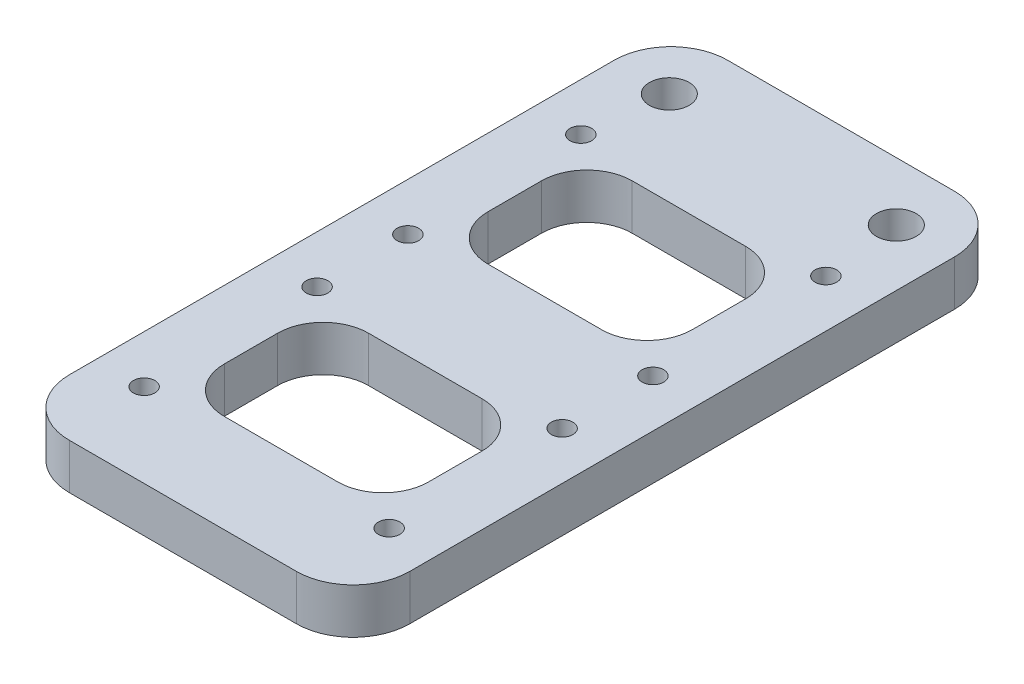
SolidWorks part; units mm, degrees
ref_plane "Front Plane" through (0, 0, 0) normal (0, 0, 1) x (1, 0, 0)
ref_plane "Top Plane" through (0, 0, 0) normal (0, 1, 0) x (1, 0, 0)
ref_plane "Right Plane" through (0, 0, 0) normal (1, 0, 0) x (0, 0, -1)
sketch "Sketch1" plane through (0, 0, 0) normal (0, 1, 0) x (1, 0, 0)
  line L1 (-15, -15) -> (15, -15)
  line L2 (-15, -15) -> (-15, 15)
  line L3 (-15, 15) -> (15, 15)
  line L4 (15, -15) -> (15, 15)
  line L5 (-15, -15) -> (15, 15) construction
  line L6 (-15, 15) -> (15, -15) construction
  point P0 (0, 0)
  dimension "D1" = 30
extrude "Boss-Extrude1" add sketch "Sketch1" along normal blind 4
sketch "Sketch3" plane through (0, 4, 0) normal (0, 1, 0) x (1, 0, 0)
  line L0 (15, -15) -> (15, 15) construction
  line L1 (-15, 15) -> (15, 15)
  line L2 (-15, 15) -> (-15, 43)
  line L3 (-15, 43) -> (15, 43)
  line L4 (15, 15) -> (15, 43)
  dimension "D1" = 28
extrude "Boss-Extrude2" add sketch "Sketch3" against normal up to surface (4 mm away) up to face at (0, 0, 0)
sketch "Sketch2" plane through (0, 4, 0) normal (0, 1, 0) x (1, 0, 0)
  line L0 (0, 0) -> (0, 50000) construction
  line L1 (-10.795, -7.62) -> (10.795, -7.62) construction
  line L2 (-10.795, -7.62) -> (-10.795, 7.62) construction
  line L3 (-10.795, 7.62) -> (10.795, 7.62) construction
  line L4 (10.795, -7.62) -> (10.795, 7.62) construction
  line L5 (-10.795, -7.62) -> (10.795, 7.62) construction
  line L6 (-10.795, 7.62) -> (10.795, -7.62) construction
  line L7 (-5, -6.3529) -> (5, -6.3529)
  line L8 (-9, -2.3529) -> (-9, 2.3529)
  line L9 (-5, 6.3529) -> (5, 6.3529)
  line L10 (9, -2.3529) -> (9, 2.3529)
  line L11 (-9, -6.3529) -> (10.795, 7.62) construction
  line L12 (-9, 6.3529) -> (9, -6.3529) construction
  line L13 (0, 23.24) -> (50000, 23.24) construction
  line L15 (-10.795, 15.62) -> (10.795, 15.62) construction
  line L16 (-10.795, 15.62) -> (-10.795, 30.86) construction
  line L17 (-10.795, 30.86) -> (10.795, 30.86) construction
  line L18 (10.795, 15.62) -> (10.795, 30.86) construction
  line L19 (-10.795, 15.62) -> (10.795, 30.86) construction
  line L20 (-10.795, 30.86) -> (10.795, 15.62) construction
  line L21 (-10, 37.86) -> (10, 37.86) construction
  line L23 (-10.795, 30.86) -> (10.795, 30.86) construction
  line L28 (-5, 16.8871) -> (5, 16.8871)
  line L29 (-9, 20.8871) -> (-9, 25.5929)
  line L30 (-5, 29.5929) -> (5, 29.5929)
  line L31 (9, 20.8871) -> (9, 25.5929)
  line L32 (-9, 16.8871) -> (9, 29.5929) construction
  line L33 (-9, 29.5929) -> (9, 16.8871) construction
  circle A0 centre (-10.795, -7.62) radius 0.95
  circle A1 centre (10.795, -7.62) radius 0.95
  circle A2 centre (10.795, 7.62) radius 0.95
  circle A3 centre (-10.795, 7.62) radius 0.95
  arc A4 (-5, -6.3529) -> (-9, -2.3529) centre (-5, -2.3529) cw
  arc A5 (5, -6.3529) -> (9, -2.3529) centre (5, -2.3529) ccw
  arc A6 (5, 6.3529) -> (9, 2.3529) centre (5, 2.3529) cw
  arc A7 (-9, 2.3529) -> (-5, 6.3529) centre (-5, 2.3529) cw
  circle A8 centre (-10.795, 30.86) radius 0.95
  circle A9 centre (10.795, 30.86) radius 0.95
  circle A10 centre (10.795, 15.62) radius 0.95
  circle A11 centre (-10.795, 15.62) radius 0.95
  circle A12 centre (-10, 37.86) radius 1.75
  circle A13 centre (10, 37.86) radius 1.75
  arc A14 (-5, 16.8871) -> (-9, 20.8871) centre (-5, 20.8871) cw
  arc A15 (5, 29.5929) -> (9, 25.5929) centre (5, 25.5929) cw
  arc A16 (5, 16.8871) -> (9, 20.8871) centre (5, 20.8871) ccw
  arc A17 (-9, 25.5929) -> (-5, 29.5929) centre (-5, 25.5929) cw
  point P0 (0, 0)
  point P10 (0, 0)
  point P11 (-9.4887, 39.11)
  point P31 (0, 23.24)
  point P40 (0, 37.86)
  point P47 (0, 23.24)
  dimension "D2" = 15.24
  dimension "D4" = 4
  dimension "D9" = 4
  dimension "D3" = 1.9
  dimension "D11" = 3.5
  dimension "D5" = 21.59
  dimension "D6" = 15.24
  dimension "D7" = 8
  dimension "D8" = 7
  dimension "D10" = 18
  dimension "D12" = 20
extrude "Cut-Extrude1" cut sketch "Sketch2" against normal through all
fillet "Fillet1" radius 5 4 edges at (15, 2, 15) (-15, 2, 15) (15, 2, -43) (-15, 2, -43)
